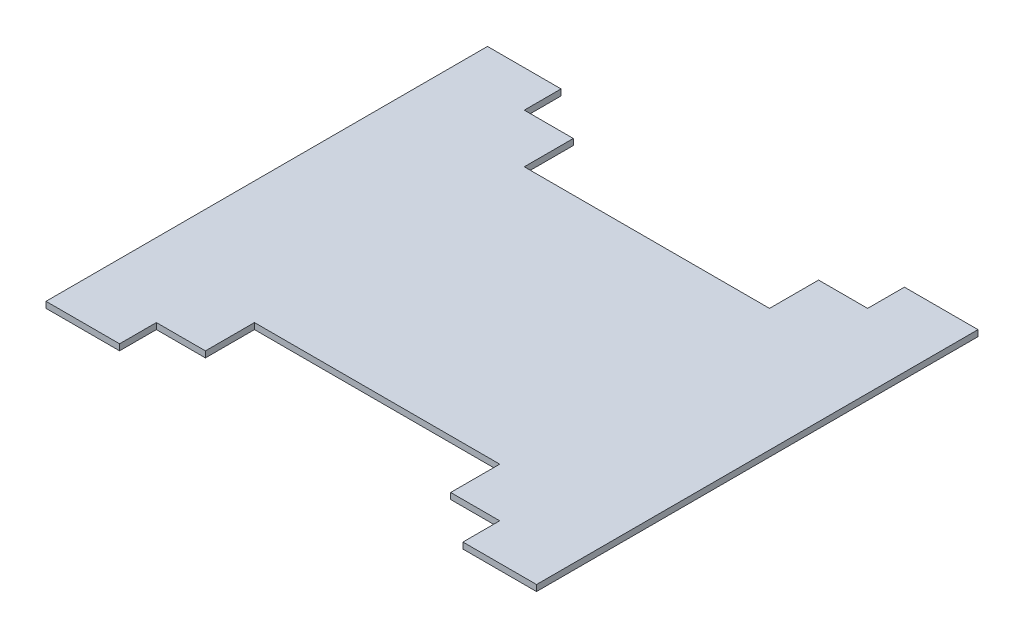
SolidWorks part; units mm, degrees
ref_plane "前基準面" through (0, 0, 0) normal (0, 0, 1) x (1, 0, 0)
ref_plane "上基準面" through (0, 0, 0) normal (0, 1, 0) x (1, 0, 0)
ref_plane "右基準面" through (0, 0, 0) normal (1, 0, 0) x (0, 0, -1)
sketch "草圖4" plane through (0, 0, 0) normal (0, 1, 0) x (1, 0, 0)
  line L0 (-200, 180) -> (-140, 180)
  line L1 (-140, 180) -> (-140, 150)
  line L2 (-140, 150) -> (-100, 150)
  line L3 (-100, 150) -> (-100, 110)
  line L4 (-100, 110) -> (100, 110)
  line L5 (100, 110) -> (100, 150)
  line L6 (100, 150) -> (140, 150)
  line L7 (140, 150) -> (140, 180)
  line L8 (140, 180) -> (200, 180)
  line L9 (-200, 180) -> (-200, -180)
  line L10 (-200, -180) -> (-140, -180)
  line L11 (-140, -180) -> (-140, -150)
  line L12 (-140, -150) -> (-100, -150)
  line L13 (-100, -150) -> (-100, -110)
  line L14 (-100, -110) -> (100, -110)
  line L15 (100, -110) -> (100, -150)
  line L16 (100, -150) -> (140, -150)
  line L17 (140, -150) -> (140, -180)
  line L18 (140, -180) -> (200, -180)
  line L19 (200, -180) -> (200, 180)
  line L20 (-100, 150) -> (100, 150) construction
  line L22 (100, -150) -> (-100, -150) construction
  line L24 (-140, 180) -> (140, 180) construction
  line L25 (140, -180) -> (-140, -180) construction
  line L27 (-100, 110) -> (100, -110) construction
  dimension "D1" = 40
  dimension "D2" = 60
  dimension "D3" = 200
  dimension "D4" = 30
  dimension "D5" = 70
  dimension "D6" = 360
  dimension "D7" = 60
  dimension "D8" = 40
extrude "伸長1" add sketch "草圖4" along normal blind 5
